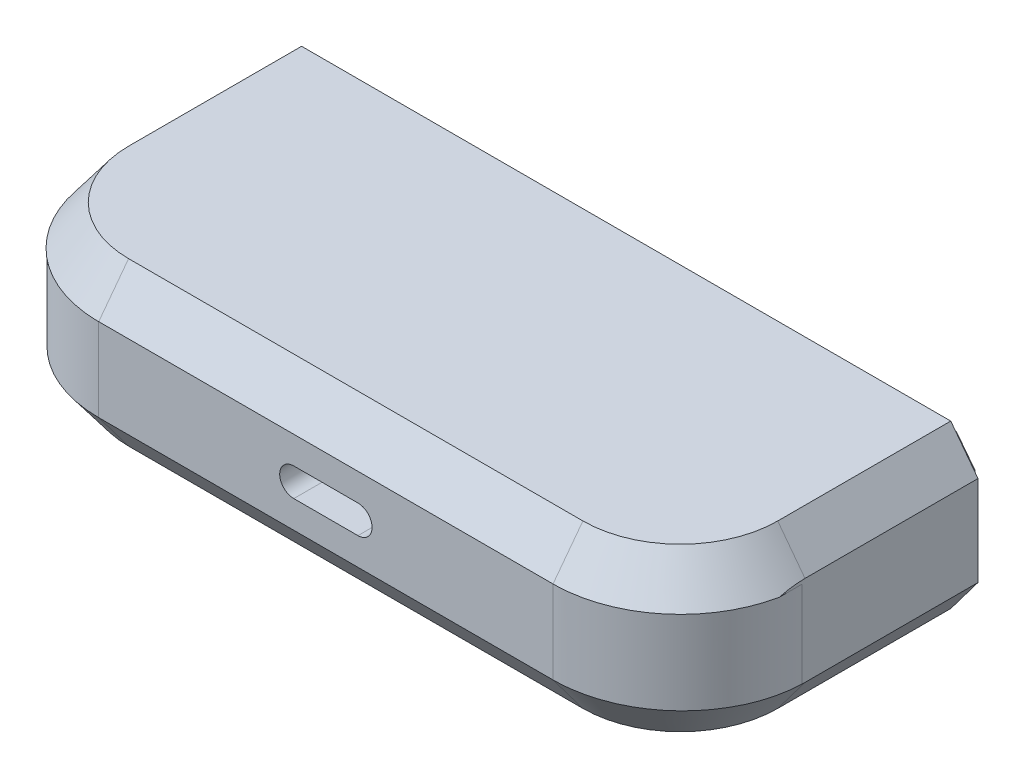
SolidWorks part; units mm, degrees
ref_plane "Front Plane" through (0, 0, 0) normal (0, 0, 1) x (1, 0, 0)
ref_plane "Top Plane" through (0, 0, 0) normal (0, 1, 0) x (1, 0, 0)
ref_plane "Right Plane" through (0, 0, 0) normal (1, 0, 0) x (0, 0, -1)
sketch "Sketch2" plane through (0, 0, 0) normal (0, 1, 0) x (1, 0, 0)
  line L0 (32.5, 11) -> (32.5, -11)
  line L1 (-23.5, -20) -> (23.5, -20)
  line L2 (-32.5, -11) -> (-32.5, 11)
  line L3 (-23.5, 20) -> (23.5, 20)
  arc A0 (23.5, 20) -> (32.5, 11) centre (23.5, 11) cw
  arc A1 (23.5, -20) -> (32.5, -11) centre (23.5, -11) ccw
  arc A2 (-23.5, -20) -> (-32.5, -11) centre (-23.5, -11) cw
  arc A3 (-32.5, 11) -> (-23.5, 20) centre (-23.5, 11) cw
  point P0 (0, 0)
  point P8 (32.5, 20)
  point P11 (32.5, -20)
  point P16 (-32.5, 20)
  dimension "D5" = 9
  dimension "D1" = 65
  dimension "D2" = 40
  dimension "D3" = 32.5
  dimension "D4" = 20
extrude "Boss-Extrude1" add sketch "Sketch2" along normal blind 15
sketch "Sketch16" plane through (0, 15, 0) normal (0, 1, 0) x (1, 0, 0)
  line L1 (20.9843, -17.2413) -> (-20.9843, -17.2413)
  line L2 (29.9843, -8.2413) -> (29.9843, 8.2413)
  line L3 (20.9843, 17.2413) -> (-20.9843, 17.2413)
  line L4 (-29.9843, -8.2413) -> (-29.9843, 8.2413)
  line L5 (29.9843, -17.2413) -> (-29.9843, 17.2413) construction
  line L6 (29.9843, 17.2413) -> (-29.9843, -17.2413) construction
  arc A0 (-23.5, 20) -> (-32.5, 11) centre (-23.5, 11) ccw construction
  arc A1 (29.9843, 8.2413) -> (20.9843, 17.2413) centre (20.9843, 8.2413) ccw
  arc A2 (20.9843, -17.2413) -> (29.9843, -8.2413) centre (20.9843, -8.2413) ccw
  arc A3 (-20.9843, -17.2413) -> (-29.9843, -8.2413) centre (-20.9843, -8.2413) cw
  arc A4 (-20.9843, 17.2413) -> (-29.9843, 8.2413) centre (-20.9843, 8.2413) ccw
  arc A5 (32.5, 11) -> (23.5, 20) centre (23.5, 11) ccw construction
  point P0 (0, 0)
  dimension "D1" = 9
extrude "Cut-Extrude6" cut sketch "Sketch16" against normal blind 12.07 draft 37 flip side to cut
sketch "Sketch17" plane through (0, 0, 0) normal (0, -1, 0) x (1, 0, 0)
  line L1 (23.5, -20) -> (-23.5, -20)
  line L2 (32.5, -11) -> (32.5, 11)
  line L3 (23.5, 20) -> (-23.5, 20)
  line L4 (-32.5, -11) -> (-32.5, 11)
  line L5 (32.5, -20) -> (-32.5, 20) construction
  line L6 (32.5, 20) -> (-32.5, -20) construction
  arc A0 (32.5, 11) -> (23.5, 20) centre (23.5, 11) ccw
  arc A1 (23.5, -20) -> (32.5, -11) centre (23.5, -11) ccw
  arc A2 (-23.5, -20) -> (-32.5, -11) centre (-23.5, -11) cw
  arc A3 (-23.5, 20) -> (-32.5, 11) centre (-23.5, 11) ccw
  point P0 (0, 0)
  dimension "D1" = 9
extrude "Boss-Extrude5" add sketch "Sketch17" against normal up to vertex (11.339 mm away)
ref_plane "Plane2" through (0, 11.339, 0) normal (0, 1, 0) x (1, 0, 0)
sketch "Sketch19" plane through (0, 11.339, 0) normal (0, 1, 0) x (1, 0, 0)
  line L1 (21, -20) -> (-21, -20)
  line L2 (32.5, -8.5) -> (32.5, 8.5)
  line L3 (21, 20) -> (-21, 20)
  line L4 (-32.5, -8.5) -> (-32.5, 8.5)
  line L5 (32.5, -20) -> (-32.5, 20) construction
  line L6 (32.5, 20) -> (-32.5, -20) construction
  arc A0 (32.5, 8.5) -> (21, 20) centre (21, 8.5) ccw
  arc A1 (21, -20) -> (32.5, -8.5) centre (21, -8.5) ccw
  arc A2 (-21, -20) -> (-32.5, -8.5) centre (-21, -8.5) cw
  arc A3 (-21, 20) -> (-32.5, 8.5) centre (-21, 8.5) ccw
  point P0 (0, 0)
  dimension "D1" = 11.5
extrude "Cut-Extrude7" cut sketch "Sketch19" against normal blind 12.07 flip side to cut
ref_plane "Plane3" through (0, 7.5, 0) normal (0, -1, 0) x (-1, 0, 0)
mirror "Mirror2" about plane through (0, 7.5, 0) normal (0, -1, 0) of "Cut-Extrude6"
sketch "Sketch20" plane through (0, 0, 20) normal (0, 0, 1) x (1, 0, 0)
  line L0 (-2.9626, 7.5) -> (2.9626, 7.5) construction
  line L1 (-2.9626, 8.805) -> (2.9626, 8.805)
  line L2 (-2.9626, 6.195) -> (2.9626, 6.195)
  arc A0 (-2.9626, 8.805) -> (-2.9626, 6.195) centre (-2.9626, 7.5) ccw
  arc A1 (2.9626, 6.195) -> (2.9626, 8.805) centre (2.9626, 7.5) ccw
  point P2 (0, 7.5)
  point P7 (0, 0)
extrude "Cut-Extrude8" cut sketch "Sketch20" against normal blind 5
sketch "Sketch21" plane through (0, 15, 0) normal (0, 1, 0) x (1, 0, 0)
  line L0 (-32.5, 8.2413) -> (32.5, 8.2413)
  line L1 (32.5, 8.2413) -> (32.5, 23.031)
  line L2 (32.5, 23.031) -> (-32.5, 23.031)
  line L3 (-32.5, 23.031) -> (-32.5, 8.2413)
extrude "Cut-Extrude9" cut sketch "Sketch21" against normal through all
sketch "Sketch24" plane through (0, 0, -8.2413) normal (0, 0, -1) x (-1, 0, 0)
  line L0 (-29.9843, 13.946) -> (29.9843, 13.946)
  line L1 (29.9843, 13.946) -> (31.7405, 11.6616)
  line L2 (31.7405, 11.6616) -> (31.7405, 3.3384)
  line L6 (-29.9843, 1.054) -> (29.9843, 1.054)
  line L7 (-29.9843, 13.946) -> (-31.7405, 11.6616)
  line L8 (-31.7405, 11.6616) -> (-31.7405, 3.3384)
  line L9 (29.9843, 1.054) -> (31.7405, 3.3384)
  line L10 (-29.9843, 1.054) -> (-31.7405, 3.3384)
extrude "Cut-Extrude10" cut sketch "Sketch24" against normal blind 0.5 flip side to cut
sketch "Sketch26" plane through (0, 0, -8.2413) normal (0, 0, -1) x (-1, 0, 0)
  spline S0 degree 3 poles (-23.7536, 11.7286) (-25.6777, 12.3672) (-27.8221, 11.7805) (-29.2164, 9.6195) (-28.7306, 6.6742) (-26.7091, 4.8345) (-23.493, 3.504) (-19.2431, 3.1053) (-14.2416, 4.5498) (-12.4104, 9.165) (-14.3682, 12.6954) (-18.1937, 13.6349) (-20.8983, 11.1748) (-23.7536, 11.7286) (-25.6777, 12.3672) (-27.8221, 11.7805) knots -0.195105 -0.120465 -0.042005 0 0.023599 0.114504 0.15025 0.234094 0.295688 0.402182 0.540873 0.636632 0.716932 0.804895 0.879535 0.957995 1 1.023599 1.114504 1.15025 only from (-25.9328, 12.2288) to (-25.9328, 12.2288)
  point P2 (-23.3662, 3.786)
  point P3 (-23.4112, 3.3807)
  point P4 (0, 0)
  point P6 (-24.0416, 3.831)
extrude "Cut-Extrude11" cut sketch "Sketch26" against normal blind 13.5
